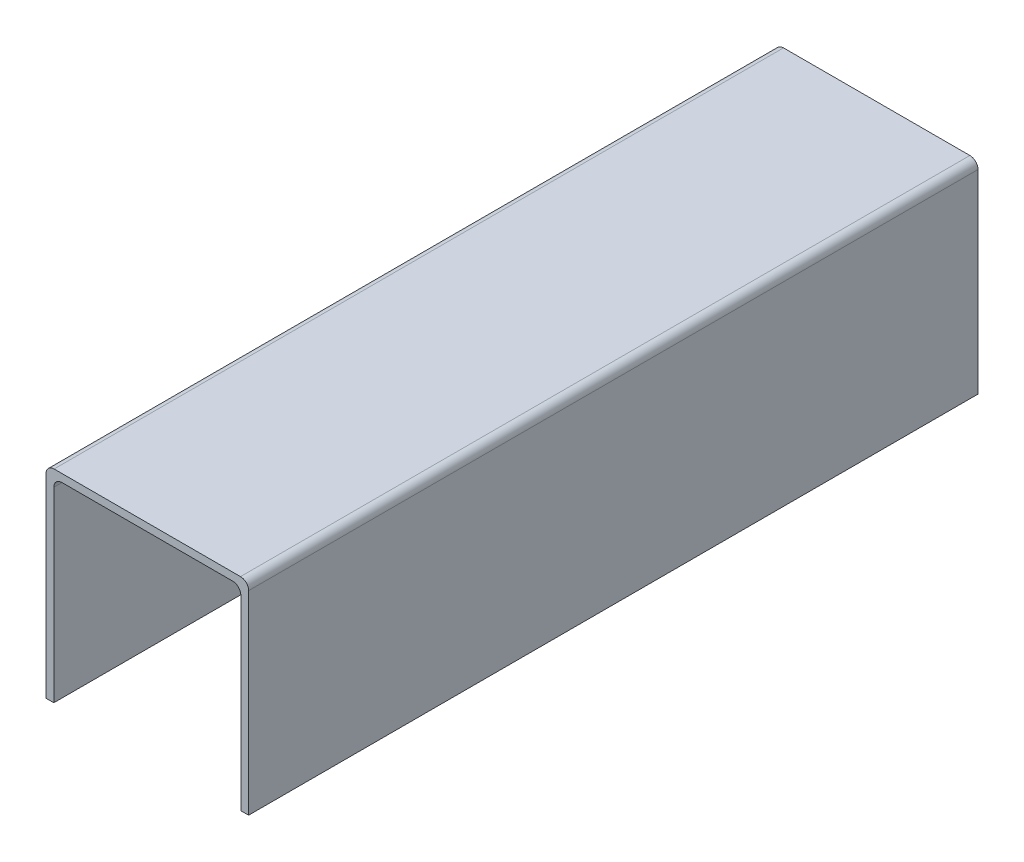
SolidWorks part; units mm, degrees
material "7075-T6 (SN)"
ref_plane "Front Plane" through (0, 0, 0) normal (0, 0, 1) x (1, 0, 0)
ref_plane "Top Plane" through (0, 0, 0) normal (0, 1, 0) x (1, 0, 0)
ref_plane "Right Plane" through (0, 0, 0) normal (1, 0, 0) x (0, 0, -1)
sketch "Sketch1" plane through (0, 0, 0) normal (0, 0, 1) x (1, 0, 0)
  line L0 (0, 0) -> (0, 50)
  line L1 (0, 50) -> (50, 50)
  line L2 (50, 50) -> (50, 0)
  line L3 (50, 0) -> (48.0722, 0)
  line L4 (48.0722, 0) -> (48.0722, 48.0722)
  line L5 (48.0722, 48.0722) -> (1.9278, 48.0722)
  line L6 (1.9278, 48.0722) -> (1.9278, 0)
  line L7 (1.9278, 0) -> (0, 0)
  line L8 (1.9278, 48.0722) -> (1.9278, 50) construction
  dimension "D1" = 50
  dimension "D2" = 1.9278
extrude "Boss-Extrude1" add sketch "Sketch1" along normal blind 180
fillet "Fillet1" radius 2 4 edges at (1.9278, 48.0722, 90) (48.0722, 48.0722, 90) (0, 50, 90) (50, 50, 90)
